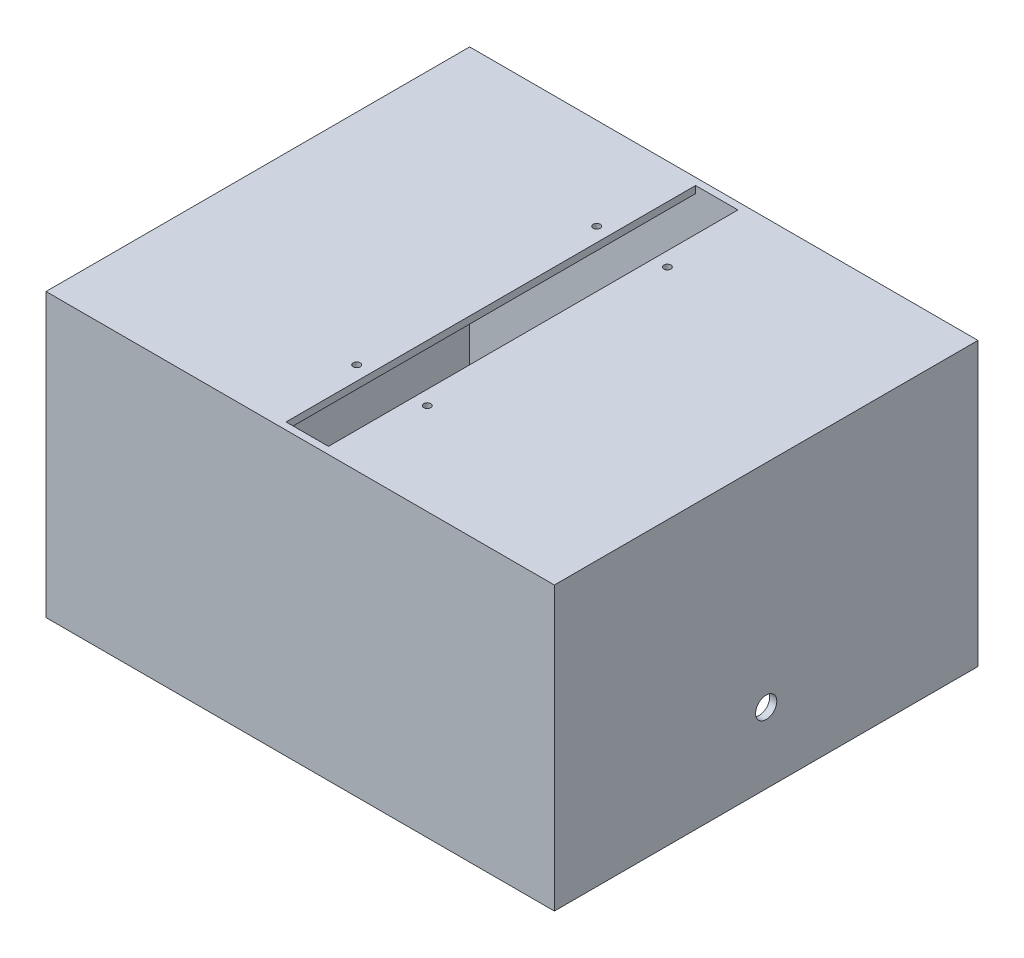
SolidWorks part; units mm, degrees
ref_plane "Front Plane" through (0, 0, 0) normal (0, 0, 1) x (1, 0, 0)
ref_plane "Top Plane" through (0, 0, 0) normal (0, 1, 0) x (1, 0, 0)
ref_plane "Right Plane" through (0, 0, 0) normal (1, 0, 0) x (0, 0, -1)
sketch "Sketch1" plane through (0, 0, 0) normal (0, 1, 0) x (1, 0, 0)
  line L0 (250, 0) -> (0, 0) construction
  line L1 (0, 0) -> (-250, 0) construction
  line L2 (-180, -150) -> (180, -150)
  line L3 (-180, -150) -> (-180, 150)
  line L4 (180, -150) -> (180, 150)
  line L5 (-180, 150) -> (180, 150)
  line L6 (-180, -150) -> (180, 150) construction
  line L7 (180, -150) -> (-180, 150) construction
  dimension "D1" = 300
  dimension "D2" = 360
extrude "Boss-Extrude1" add sketch "Sketch1" against normal blind 200
sketch "Sketch2" plane through (0, -200, 0) normal (0, -1, 0) x (1, 0, 0)
  line L0 (-180, 150) -> (180, 150) construction
  line L1 (-175, -145) -> (175, -145)
  line L2 (-175, -145) -> (-175, 145)
  line L3 (-175, 145) -> (175, 145)
  line L4 (175, -145) -> (175, 145)
  line L5 (-175, -145) -> (175, 145) construction
  line L6 (-175, 145) -> (175, -145) construction
  line L7 (180, 150) -> (180, -150) construction
  point P0 (0, 0)
  dimension "D1" = 5
  dimension "D2" = 5
extrude "Cut-Extrude1" cut sketch "Sketch2" against normal blind 195
sketch "Sketch3" plane through (0, 0, 0) normal (0, 1, 0) x (1, 0, 0)
  line L0 (-180, 0) -> (180, 0) construction
  line L1 (-180, 150) -> (-180, -150) construction
  line L2 (180, -150) -> (180, 150) construction
  line L3 (0, 150) -> (0, -120.2082) construction
  line L4 (-15, -145) -> (15, -145)
  line L5 (-15, -145) -> (-15, 145)
  line L6 (-15, 145) -> (15, 145)
  line L7 (15, -145) -> (15, 145)
  line L8 (-15, -145) -> (15, 145) construction
  line L9 (-15, 145) -> (15, -145) construction
  line L10 (180, 150) -> (-180, 150) construction
  point P6 (0, 0)
  dimension "D1" = 30
  dimension "D2" = 5
extrude "Cut-Extrude2" cut sketch "Sketch3" against normal through all
sketch "Sketch4" plane through (-180, 0, 0) normal (-1, 0, 0) x (0, 0, 1)
  line L0 (0, 0) -> (0, -200) construction
  line L1 (-150, -200) -> (150, -200) construction
  circle A0 centre (0, -150) radius 7.5
  point P7 (0, -100)
  point P8 (0, -100)
  point P10 (0, -150)
  dimension "D1" = 50
  dimension "D2" = 15
extrude "Cut-Extrude3" cut sketch "Sketch4" against normal through all
sketch "Sketch5" plane through (0, 0, 0) normal (0, 1, 0) x (1, 0, 0)
  line L0 (0, 150) -> (0, -150) construction
  line L1 (180, 150) -> (-180, 150) construction
  line L2 (-180, -150) -> (180, -150) construction
  line L3 (25, 150) -> (25, -150) construction
  line L4 (-25, 150) -> (-25, -150) construction
  line L5 (-180, 0) -> (180, 0) construction
  line L6 (-180, 150) -> (-180, -150) construction
  line L7 (180, -150) -> (180, 150) construction
  circle A0 centre (-25, 85) radius 2.5
  circle A1 centre (25, 85) radius 2.5
  circle A2 centre (25, -85) radius 2.5
  circle A3 centre (-25, -85) radius 2.5
  dimension "D4" = 5
  dimension "D1" = 25
  dimension "D2" = 25
  dimension "D3" = 85
extrude "Cut-Extrude4" cut sketch "Sketch5" against normal up to surface (5 mm away) up to face at (-95, -5, 0)
